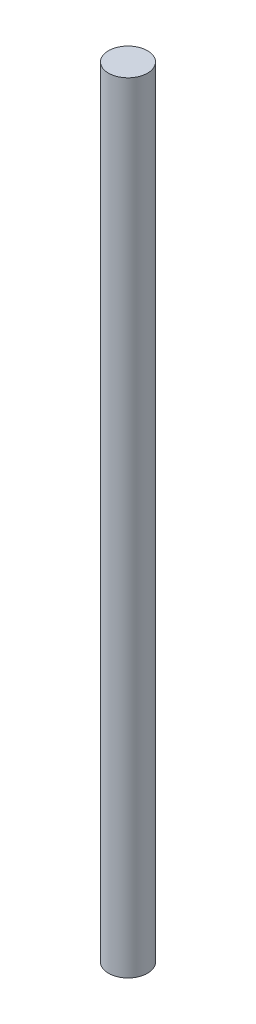
SolidWorks part; units mm, degrees
ref_plane "Front Plane" through (0, 0, 0) normal (0, 0, 1) x (1, 0, 0)
ref_plane "Top Plane" through (0, 0, 0) normal (0, 1, 0) x (1, 0, 0)
ref_plane "Right Plane" through (0, 0, 0) normal (1, 0, 0) x (0, 0, -1)
sketch "Sketch1" plane through (0, 0, 0) normal (0, 1, 0) x (1, 0, 0)
  line L1 (0.625, -0.625) -> (-0.625, -0.625) construction
  line L2 (0.625, -0.625) -> (0.625, 0.625) construction
  line L3 (0.625, 0.625) -> (-0.625, 0.625) construction
  line L4 (-0.625, -0.625) -> (-0.625, 0.625) construction
  circle A0 centre (0, 0) radius 0.625
  point P0 (0, 0)
  point P7 (0, 0.625)
  point P9 (-0.625, 0)
  dimension "D1" = 1.25
  dimension "D2" = 1.25
extrude "Boss-Extrude1" add sketch "Sketch1" along normal blind 25
